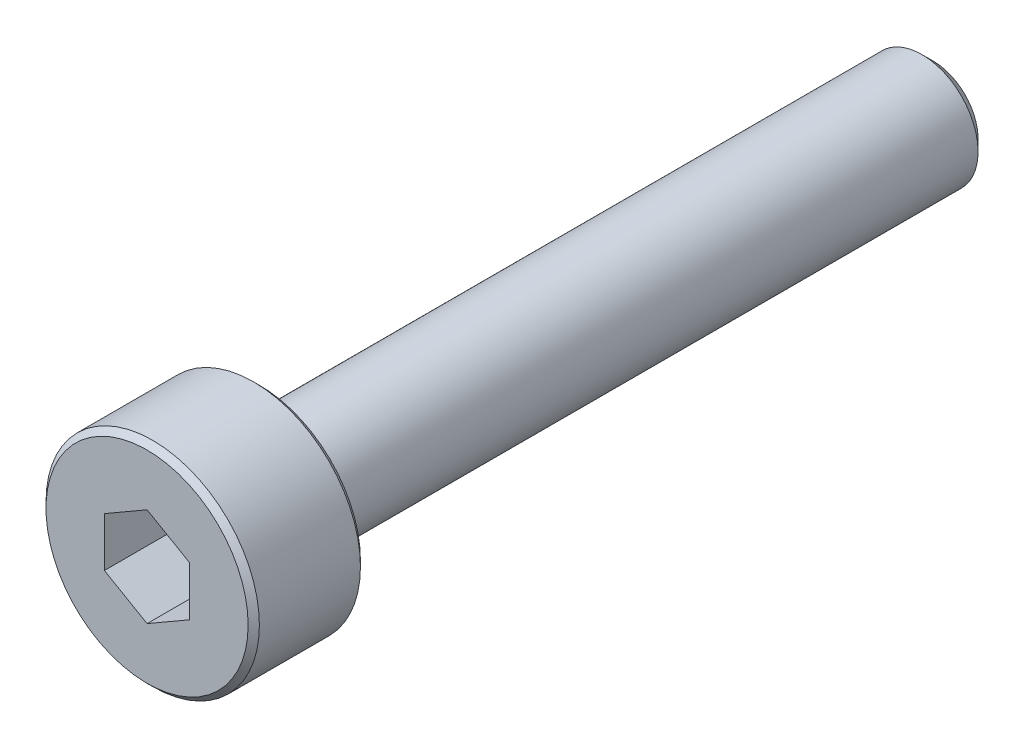
SolidWorks part; units mm, degrees
ref_plane "前视基准面" through (0, 0, 0) normal (0, 0, 1) x (1, 0, 0)
ref_plane "上视基准面" through (0, 0, 0) normal (0, 1, 0) x (1, 0, 0)
ref_plane "右视基准面" through (0, 0, 0) normal (1, 0, 0) x (0, 0, -1)
other "Configuration Table"
sketch "草图1" plane through (0, 0, 0) normal (0, 1, 0) x (1, 0, 0)
  line L0 (1.9, -10) -> (0, -10)
  line L1 (0, -10) -> (0, -12)
  line L2 (0, -12) -> (1.9, -12)
  line L3 (1.9, -12) -> (1.9, -10)
  line L4 (0, -10) -> (0, -12) construction
revolve "旋转1" add sketch "草图1" angle 360 about L4
sketch "草图2" plane through (0, 0, 10) normal (0, 0, -1) x (-1, 0, 0)
  circle A0 centre (0, 0) radius 1
extrude "凸台-拉伸1" add sketch "草图2" along normal blind 12
sketch "草图3" plane through (0, 0, 12) normal (0, 0, 1) x (1, 0, 0)
  line L0 (-0.76, -0.4388) -> (0, -0.8776)
  line L1 (0, -0.8776) -> (0.76, -0.4388)
  line L2 (0.76, -0.4388) -> (0.76, 0.4388)
  line L3 (0.76, 0.4388) -> (0, 0.8776)
  line L4 (0, 0.8776) -> (-0.76, 0.4388)
  line L5 (-0.76, 0.4388) -> (-0.76, -0.4388)
extrude "切除-拉伸1" cut sketch "草图3" against normal blind 1.5
chamfer "倒角1" distance 0.1 angle 45 2 edges at (1.9, 0, 10) (1.9, 0, 12)
chamfer "倒角2" distance 0.2 angle 45 1 edges at (-1, 0, -2)
